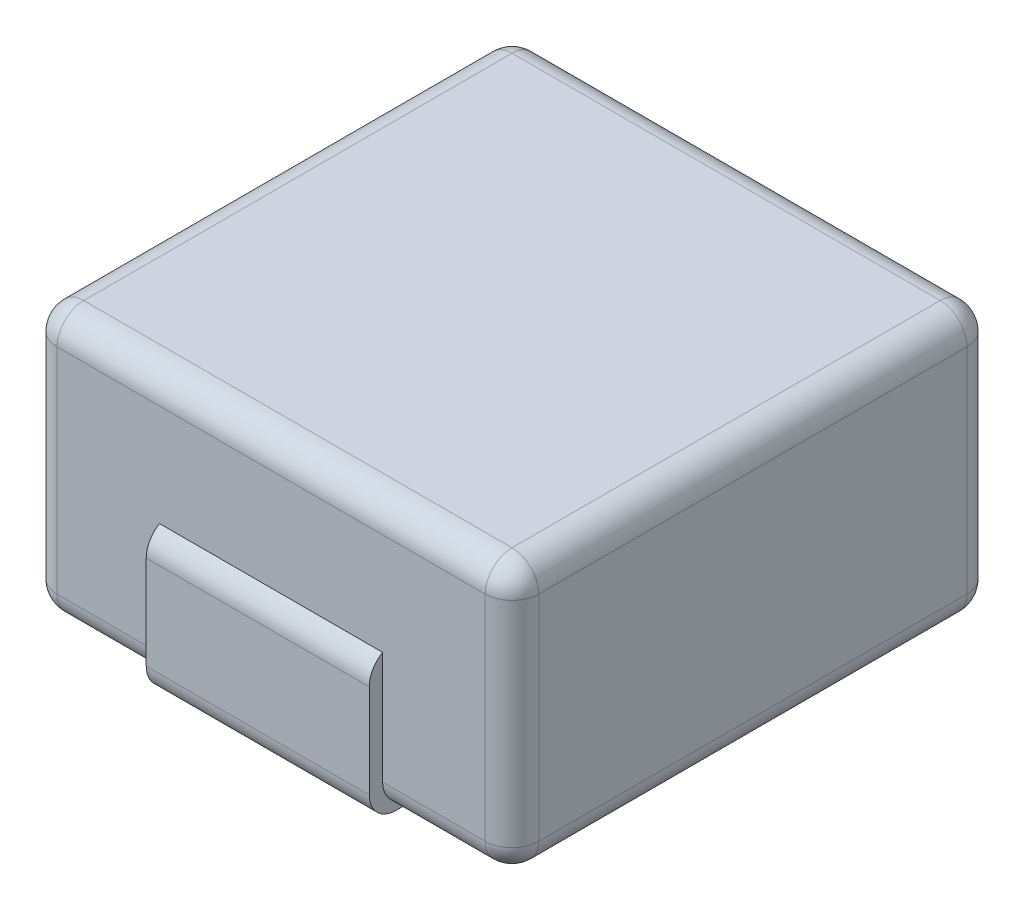
SolidWorks part; units mm, degrees
ref_plane "Front" through (0, 0, 0) normal (0, 0, 1) x (1, 0, 0)
ref_plane "Top" through (0, 0, 0) normal (0, 1, 0) x (1, 0, 0)
ref_plane "Right" through (0, 0, 0) normal (1, 0, 0) x (0, 0, -1)
ref_plane "Плоскость1" through (0, 0.05, 0) normal (0, 1, 0) x (1, 0, 0)
sketch "Эскиз1" plane through (0, 0.05, 0) normal (0, 1, 0) x (1, 0, 0)
  line L1 (-2.7, 2.7) -> (2.7, 2.7)
  line L2 (-2.7, 2.7) -> (-2.7, -2.7)
  line L3 (-2.7, -2.7) -> (2.7, -2.7)
  line L4 (2.7, 2.7) -> (2.7, -2.7)
  line L5 (-2.7, 2.7) -> (2.7, -2.7) construction
  line L6 (-2.7, -2.7) -> (2.7, 2.7) construction
  point P0 (0, 0)
  dimension "D1" = 5.4
  dimension "D2" = 5.4
extrude "Бобышка-Вытянуть1" add sketch "Эскиз1" along normal blind 3
fillet "Скругление1" radius 0.3 12 edges at (0, 3.05, 2.7) (-2.7, 3.05, 0) (0, 3.05, -2.7) (2.7, 3.05, 0) (0, 0.05, 2.7) (2.7, 0.05, 0) (0, 0.05, -2.7) (-2.7, 0.05, 0) (-2.7, 1.55, -2.7) (2.7, 1.55, -2.7) (-2.7, 1.55, 2.7) (2.7, 1.55, 2.7)
sketch "Эскиз2" plane through (0, 0.05, 0) normal (0, -1, 0) x (1, 0, 0)
  line L0 (-2.4, 2.7) -> (2.4, 2.7) construction
  line L1 (-1.25, 2.85) -> (1.25, 2.85)
  line L2 (-1.25, 2.85) -> (-1.25, 1.45)
  line L3 (-1.25, 1.45) -> (1.25, 1.45)
  line L4 (1.25, 2.85) -> (1.25, 1.45)
  line L5 (-1.25, -1.45) -> (1.25, -1.45)
  line L6 (-1.25, -1.45) -> (-1.25, -2.85)
  line L7 (-1.25, -2.85) -> (1.25, -2.85)
  line L8 (1.25, -1.45) -> (1.25, -2.85)
  line L9 (2.4, -2.7) -> (-2.4, -2.7) construction
  point P12 (0, 2.85)
  dimension "D1" = 2.5
  dimension "D2" = 1.4
  dimension "D3" = 0.15
  dimension "D4" = 1.4
  dimension "D5" = 0.15
extrude "Бобышка-Вытянуть2" add sketch "Эскиз2" along normal blind 0.05 and the other way blind 1.6 separate body
fillet "Скругление2" radius 0.3 2 edges at (0, 1.65, 2.85) (0, 0, 2.85)
fillet "Скругление3" radius 0.3 2 edges at (0, 1.65, -2.85) (0, 0, -2.85)
